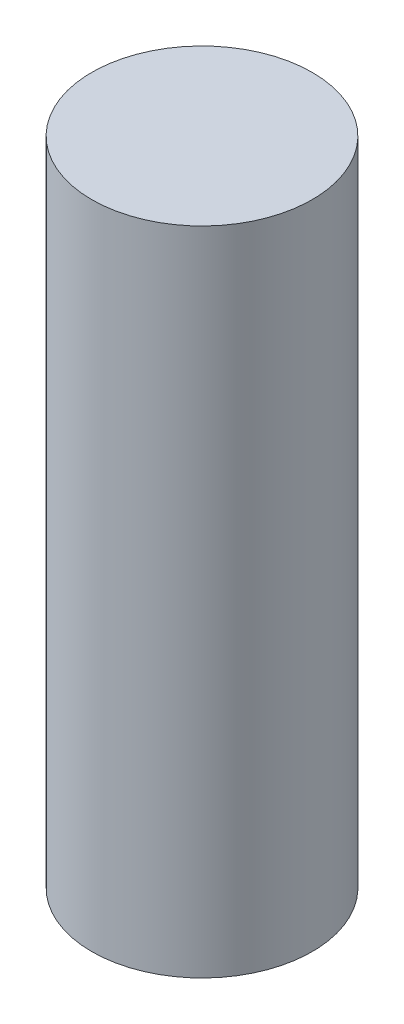
SolidWorks part; units mm, degrees
ref_plane "Front Plane" through (0, 0, 0) normal (0, 0, 1) x (1, 0, 0)
ref_plane "Top Plane" through (0, 0, 0) normal (0, 1, 0) x (1, 0, 0)
ref_plane "Right Plane" through (0, 0, 0) normal (1, 0, 0) x (0, 0, -1)
sketch "Sketch1" plane through (0, 0, 0) normal (0, 1, 0) x (1, 0, 0)
  circle A0 centre (0, 0) radius 11.85
  dimension "D1" = 23.7
extrude "Boss-Extrude1" add sketch "Sketch1" along normal blind 70
